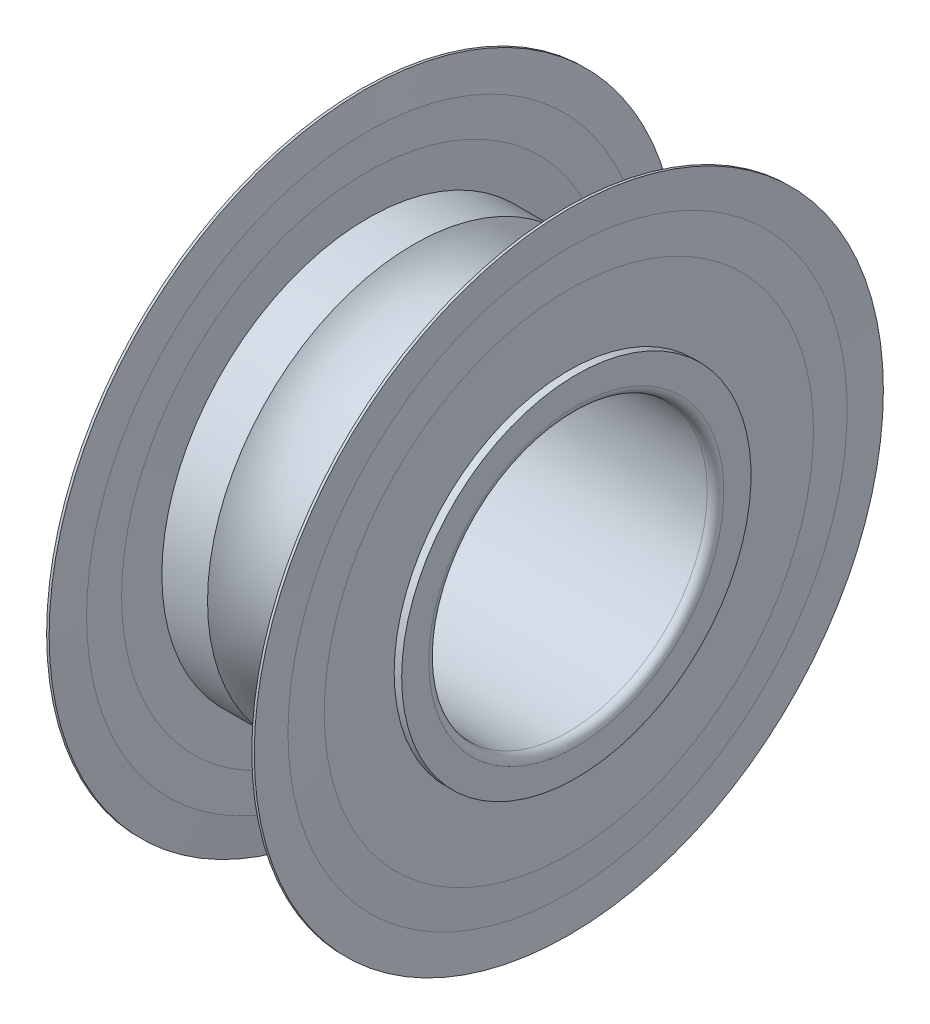
SolidWorks part; units mm, degrees
material "Chrome Stainless Steel"
ref_plane "Front Plane" through (0, 0, 0) normal (0, 0, 1) x (1, 0, 0)
ref_plane "Top Plane" through (0, 0, 0) normal (0, 1, 0) x (1, 0, 0)
ref_plane "Right Plane" through (0, 0, 0) normal (1, 0, 0) x (0, 0, -1)
ref_plane "Plane1" through (0, 0, 0) normal (0, 0, 1) x (1, 0, 0)
sketch "Sketch1" plane through (0, 0, 0) normal (0, 0, 1) x (1, 0, 0)
  line L0 (0, 7.3) -> (0, 5.3)
  line L1 (0.3, 5) -> (7.7, 5)
  line L2 (8, 5.3) -> (8, 7.3)
  line L3 (7.9, 7.4) -> (5.8491, 7.4)
  line L4 (2.1509, 7.4) -> (0.1, 7.4)
  line L5 (50, 0) -> (-50, 0) construction
  arc A0 (0, 5.3) -> (0.3, 5) centre (0.3, 5.3) ccw
  arc A1 (7.7, 5) -> (8, 5.3) centre (7.7, 5.3) ccw
  arc A2 (8, 7.3) -> (7.9, 7.4) centre (7.9, 7.3) ccw
  arc A3 (5.8491, 7.4) -> (2.1509, 7.4) centre (4, 8.9) cw
  arc A4 (0.1, 7.4) -> (0, 7.3) centre (0.1, 7.3) ccw
revolve "Revolve1" add sketch "Sketch1" angle 360 about L5
ref_plane "Plane2" through (0, 0, 0) normal (0, 0, 1) x (1, 0, 0)
sketch "Sketch2" plane through (0, 0, 0) normal (0, 0, 1) x (1, 0, 0)
  line L0 (0, 9.975) -> (0, 6.275)
  line L1 (0, 6.275) -> (0.285, 6.275)
  line L2 (0.51, 6.5) -> (0.51, 9.525)
  line L3 (0.51, 9.525) -> (7.49, 9.525)
  line L4 (7.49, 9.525) -> (7.49, 6.5)
  line L5 (7.715, 6.275) -> (8, 6.275)
  line L6 (8, 6.275) -> (8, 9.975)
  line L7 (8, 9.975) -> (0, 9.975)
  line L8 (50, 0) -> (-50, 0) construction
  arc A0 (0.285, 6.275) -> (0.51, 6.5) centre (0.285, 6.5) ccw
  arc A1 (7.49, 6.5) -> (7.715, 6.275) centre (7.715, 6.5) ccw
revolve "Cut-Revolve1" cut sketch "Sketch2" angle 360 about L8
ref_plane "Plane3" through (0, 0, 0) normal (0, 0, 1) x (1, 0, 0)
sketch "Sketch3" plane through (0, 0, 0) normal (0, 0, 1) x (1, 0, 0)
  line L0 (0.27, 11.3) -> (0.315, 10.0438)
  line L1 (0.315, 10.0438) -> (0.27, 8.7875)
  line L2 (0.27, 8.7875) -> (0.27, 6.275)
  line L3 (0.27, 6.275) -> (0.36, 6.275)
  line L4 (0.36, 6.275) -> (0.45, 8.7875)
  line L5 (0.45, 8.7875) -> (0.45, 10.0438)
  line L6 (0.45, 10.0438) -> (0.36, 11.3)
  line L7 (0.36, 11.3) -> (0.27, 11.3)
  line L8 (50, 0) -> (-50, 0) construction
revolve "Revolve2" add sketch "Sketch3" angle 360 about L8
ref_plane "Plane4" through (0, 0, 0) normal (0, 0, 1) x (1, 0, 0)
sketch "Sketch4" plane through (0, 0, 0) normal (0, 0, 1) x (1, 0, 0)
  line L0 (7.55, 10.0438) -> (7.55, 8.7875)
  line L1 (7.55, 8.7875) -> (7.64, 6.275)
  line L2 (7.64, 6.275) -> (7.73, 6.275)
  line L3 (7.73, 6.275) -> (7.73, 8.7875)
  line L4 (7.73, 8.7875) -> (7.685, 10.0438)
  line L5 (7.685, 10.0438) -> (7.73, 11.3)
  line L6 (7.73, 11.3) -> (7.64, 11.3)
  line L7 (7.64, 11.3) -> (7.55, 10.0438)
  line L8 (50, 0) -> (-50, 0) construction
revolve "Revolve3" add sketch "Sketch4" angle 360 about L8
